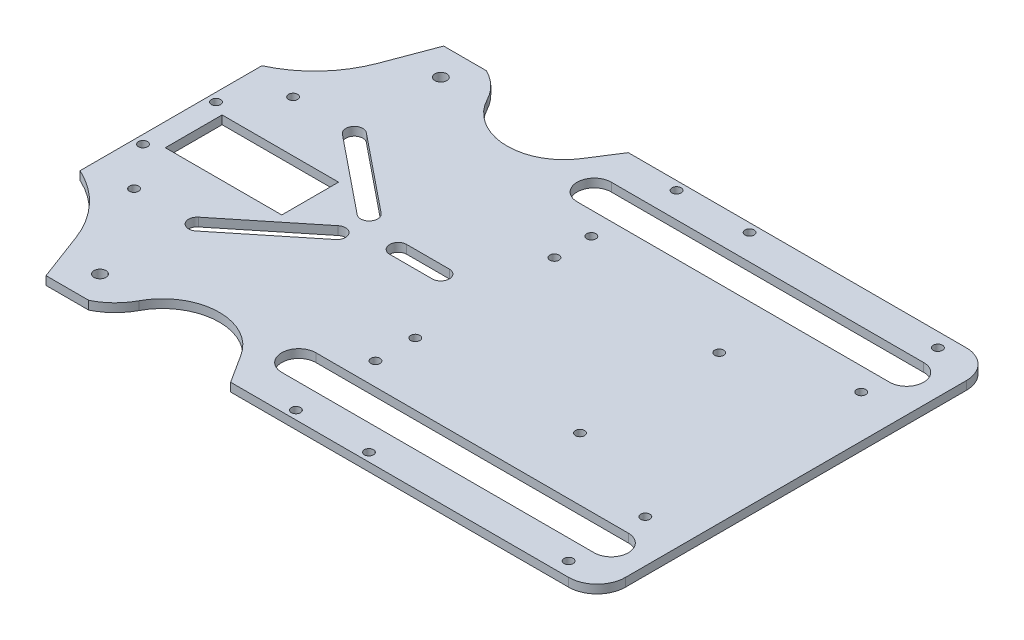
SolidWorks part; units mm, degrees
ref_plane "Front Plane" through (0, 0, 0) normal (0, 0, 1) x (1, 0, 0)
ref_plane "Top Plane" through (0, 0, 0) normal (0, 1, 0) x (1, 0, 0)
ref_plane "Right Plane" through (0, 0, 0) normal (1, 0, 0) x (0, 0, -1)
sketch "Çizim16" plane through (0, 0, 0) normal (0, 1, 0) x (1, 0, 0)
  line L1 (-110, -70) -> (100, -70)
  line L2 (-110, -70) -> (-110, 70)
  line L3 (-110, 70) -> (100, 70)
  line L4 (110, -60) -> (110, 60)
  line L5 (-110, -70) -> (110, 70) construction
  line L6 (-110, 70) -> (110, -70) construction
  arc A0 (100, -70) -> (110, -60) centre (100, -60) ccw
  arc A1 (100, 70) -> (110, 60) centre (100, 60) cw
  point P0 (0, 0)
  dimension "D3" = 10
  dimension "D1" = 220
  dimension "D2" = 140
extrude "Yükseklik-Ekstrüzyon3" add sketch "Çizim16" along normal blind 3
sketch "Çizim18" plane through (0, 3, 0) normal (0, 1, 0) x (1, 0, 0)
  line L0 (-19, 70) -> (-25.4638, 59.8897)
  line L1 (100, 70) -> (-110, 70) construction
  line L2 (-69, 70) -> (-19, 70)
  line L3 (-110, 70) -> (-110, -70) construction
  arc A0 (-25.4638, 59.8897) -> (-60, 61.3236) centre (-42.3144, 70.6627) cw
  arc A1 (-60, 61.3236) -> (-69, 70) centre (-77.6856, 51.9844) ccw
  dimension "D3" = 20
  dimension "D4" = 20
  dimension "D1" = 50
  dimension "D2" = 12
  dimension "D5" = 41
  dimension "D6" = 50
extrude "Kes-Ekstrüzyon10" cut sketch "Çizim18" against normal blind 3
sketch "Çizim19" plane through (0, 3, 0) normal (0, 1, 0) x (1, 0, 0)
  line L0 (-19, -70) -> (-25.4638, -59.8897)
  line L1 (-110, -70) -> (100, -70) construction
  line L2 (-69, -70) -> (-19, -70)
  line L3 (-110, 70) -> (-110, -70) construction
  arc A0 (-25.4638, -59.8897) -> (-60, -61.3236) centre (-42.3144, -70.6627) ccw
  arc A1 (-60, -61.3236) -> (-69, -70) centre (-77.6856, -51.9844) cw
  dimension "D1" = 20
  dimension "D3" = 20
  dimension "D2" = 12
  dimension "D4" = 50
  dimension "D5" = 41
  dimension "D6" = 50
extrude "Kes-Ekstrüzyon11" cut sketch "Çizim19" against normal blind 3
sketch "Çizim23" plane through (0, 3, 0) normal (0, 1, 0) x (1, 0, 0)
  line L0 (-84, -70) -> (-90.3297, -53.1496)
  line L1 (-110, -70) -> (-69, -70) construction
  line L2 (-110, 70) -> (-110, -70) construction
  line L3 (-110, -32) -> (-110, -70)
  line L4 (-110, -70) -> (-84, -70)
  arc A0 (-90.3297, -53.1496) -> (-110, -32) centre (-125.9027, -66.5124) ccw
  dimension "D2" = 38
  dimension "D1" = 18
  dimension "D3" = 38
  dimension "D4" = 26
extrude "Kes-Ekstrüzyon14" cut sketch "Çizim23" against normal blind 3
sketch "Çizim24" plane through (0, 3, 0) normal (0, 1, 0) x (1, 0, 0)
  line L0 (-84, 70) -> (-90.3297, 53.1496)
  line L1 (-69, 70) -> (-110, 70) construction
  line L2 (-110, 70) -> (-110, -32) construction
  line L3 (-110, 32) -> (-110, 70)
  line L4 (-110, 70) -> (-84, 70)
  arc A0 (-90.3297, 53.1496) -> (-110, 32) centre (-125.9027, 66.5124) cw
  dimension "D3" = 38
  dimension "D1" = 26
  dimension "D2" = 38
  dimension "D4" = 18
extrude "Kes-Ekstrüzyon15" cut sketch "Çizim24" against normal blind 3
sketch "Çizim25" plane through (0, 3, 0) normal (0, 1, 0) x (1, 0, 0)
  line L0 (-45.893, -5.6667) -> (-73.1143, -27.6667) construction
  line L1 (-44.0073, -8) -> (-71.2286, -30)
  line L2 (-47.7787, -3.3335) -> (-75, -25.3335)
  line L3 (-110, 32) -> (-110, -32) construction
  line L4 (-19, -70) -> (100, -70) construction
  line L5 (-84, -70) -> (-69, -70) construction
  arc A0 (-44.0073, -8) -> (-47.7787, -3.3335) centre (-45.893, -5.6667) ccw
  arc A1 (-75, -25.3335) -> (-71.2286, -30) centre (-73.1143, -27.6667) ccw
  point P2 (-59.5036, -16.6667)
  dimension "D2" = 3
  dimension "D4" = 62
  dimension "D1" = 35
  dimension "D3" = 35
  dimension "D5" = 40
extrude "Kes-Ekstrüzyon16" cut sketch "Çizim25" against normal blind 3
sketch "Çizim26" plane through (0, 3, 0) normal (0, 1, 0) x (1, 0, 0)
  line L0 (-73.1143, 27.6667) -> (-45.893, 5.6667) construction
  line L1 (-71.2286, 30) -> (-44.0073, 8)
  line L2 (-75, 25.3335) -> (-47.7787, 3.3335)
  line L6 (-69, 70) -> (-84, 70) construction
  line L7 (100, 70) -> (-19, 70) construction
  line L8 (-110, 32) -> (-110, -32) construction
  arc A0 (-71.2286, 30) -> (-75, 25.3335) centre (-73.1143, 27.6667) ccw
  arc A1 (-47.7787, 3.3335) -> (-44.0073, 8) centre (-45.893, 5.6667) ccw
  point P2 (-59.5036, 16.6667)
  dimension "D1" = 3
  dimension "D2" = 35
  dimension "D3" = 40
  dimension "D4" = 62
  dimension "D5" = 35
extrude "Kes-Ekstrüzyon17" cut sketch "Çizim26" against normal blind 3
sketch "Çizim27" plane through (0, 3, 0) normal (0, 1, 0) x (1, 0, 0)
  line L0 (-15, 0) -> (-30, 0) construction
  line L1 (-15, -3) -> (-30, -3)
  line L2 (-15, 3) -> (-30, 3)
  line L4 (-110, 32) -> (-110, -32) construction
  arc A0 (-15, -3) -> (-15, 3) centre (-15, 0) ccw
  arc A1 (-30, 3) -> (-30, -3) centre (-30, 0) ccw
  point P2 (-22.5, 0)
  dimension "D1" = 3
  dimension "D2" = 80
  dimension "D3" = 15
extrude "Kes-Ekstrüzyon18" cut sketch "Çizim27" against normal blind 3
sketch "Çizim28" plane through (0, 3, 0) normal (0, 1, 0) x (1, 0, 0)
  line L0 (-19, -70) -> (100, -70) construction
  circle A0 centre (1, -67) radius 1.6
  circle A1 centre (26.7, -67) radius 1.6
  dimension "D1" = 3.2
  dimension "D2" = 3.2
  dimension "D3" = 3
  dimension "D4" = 25.7
  dimension "D5" = 3
  dimension "D6" = 20
extrude "Kes-Ekstrüzyon19" cut sketch "Çizim28" against normal blind 3
sketch "Çizim29" plane through (0, 3, 0) normal (0, 1, 0) x (1, 0, 0)
  line L0 (-110, 32) -> (-110, -32) construction
  circle A0 centre (-107, 12.85) radius 1.6
  circle A1 centre (-107, -12.85) radius 1.6
  dimension "D1" = 3.2
  dimension "D2" = 3.2
  dimension "D3" = 25.7
  dimension "D4" = 3
  dimension "D5" = 3
  dimension "D6" = 19.15
extrude "Kes-Ekstrüzyon20" cut sketch "Çizim29" against normal blind 3
sketch "Çizim30" plane through (0, 3, 0) normal (0, 1, 0) x (1, 0, 0)
  line L0 (100, 70) -> (-19, 70) construction
  circle A0 centre (1, 67) radius 1.6
  circle A1 centre (26.7, 67) radius 1.6
  dimension "D1" = 3.2
  dimension "D2" = 3.2
  dimension "D3" = 3
  dimension "D4" = 3
  dimension "D5" = 25.7
  dimension "D6" = 20
extrude "Kes-Ekstrüzyon21" cut sketch "Çizim30" against normal blind 3
sketch "Çizim31" plane through (0, 3, 0) normal (0, 1, 0) x (1, 0, 0)
  line L0 (-69, 70) -> (-84, 70) construction
  line L1 (-102, -10) -> (-61, -10)
  line L2 (-102, -10) -> (-102, 10)
  line L3 (-102, 10) -> (-61, 10)
  line L4 (-61, -10) -> (-61, 10)
  line L5 (-102, -10) -> (-61, 10) construction
  line L6 (-102, 10) -> (-61, -10) construction
  line L7 (-110, 32) -> (-110, -32) construction
  point P0 (-81.5, 0)
  dimension "D1" = 41
  dimension "D2" = 20
  dimension "D3" = 60
  dimension "D4" = 8
extrude "Kes-Ekstrüzyon22" cut sketch "Çizim31" against normal blind 10
sketch "Çizim32" plane through (0, 3, 0) normal (0, 1, 0) x (1, 0, 0)
  line L0 (110, -60) -> (110, 60) construction
  line L1 (-19, -70) -> (100, -70) construction
  line L2 (100, 70) -> (-19, 70) construction
  line L3 (-84, -70) -> (-69, -70) construction
  line L4 (-110, 32) -> (-110, -32) construction
  line L5 (-69, 70) -> (-84, 70) construction
  circle A0 centre (95, -65) radius 1.6
  circle A1 centre (95, 65) radius 1.6
  circle A2 centre (-95, -28) radius 1.6
  circle A3 centre (-95, 28) radius 1.6
  dimension "D1" = 3.2
  dimension "D2" = 3.2
  dimension "D3" = 15
  dimension "D4" = 5
  dimension "D5" = 5
  dimension "D6" = 15
  dimension "D7" = 3.2
  dimension "D8" = 3.2
  dimension "D9" = 42
  dimension "D10" = 15
  dimension "D11" = 15
  dimension "D12" = 42
extrude "Kes-Ekstrüzyon23" cut sketch "Çizim32" against normal blind 10
sketch "Çizim33" plane through (0, 3, 0) normal (0, 1, 0) x (1, 0, 0)
  line L0 (97, 52) -> (-13, 52) construction
  line L1 (97, 46) -> (-13, 46)
  line L2 (97, 58) -> (-13, 58)
  line L3 (100, 70) -> (-19, 70) construction
  line L4 (110, -60) -> (110, 60) construction
  line L5 (-13, -52) -> (97, -52) construction
  line L6 (-13, -46) -> (97, -46)
  line L7 (-13, -58) -> (97, -58)
  line L8 (-19, -70) -> (100, -70) construction
  arc A0 (97, 46) -> (97, 58) centre (97, 52) ccw
  arc A1 (-13, 58) -> (-13, 46) centre (-13, 52) ccw
  arc A2 (-13, -46) -> (-13, -58) centre (-13, -52) ccw
  arc A3 (97, -58) -> (97, -46) centre (97, -52) ccw
  point P2 (42, 52)
  point P13 (42, -52)
  dimension "D2" = 6
  dimension "D4" = 13
  dimension "D5" = 6
  dimension "D8" = 13
  dimension "D1" = 110
  dimension "D3" = 12
  dimension "D6" = 110
  dimension "D7" = 12
extrude "Kes-Ekstrüzyon24" cut sketch "Çizim33" against normal blind 10
sketch "Çizim34" plane through (0, 3, 0) normal (0, 1, 0) x (1, 0, 0)
  line L0 (-84, -70) -> (-69, -70) construction
  line L1 (-110, 32) -> (-110, -32) construction
  line L2 (-69, 70) -> (-84, 70) construction
  circle A0 centre (-75, -60) radius 2.1
  circle A1 centre (-75, 60) radius 2.1
  dimension "D1" = 4.2
  dimension "D2" = 4.2
  dimension "D3" = 10
  dimension "D4" = 35
  dimension "D5" = 35
  dimension "D6" = 10
extrude "Kes-Ekstrüzyon25" cut sketch "Çizim34" against normal blind 3
sketch "Çizim35" plane through (0, 3, 0) normal (0, 1, 0) x (1, 0, 0)
  line L0 (97, -46) -> (-13, -46) construction
  line L1 (-13, 46) -> (97, 46) construction
  line L2 (110, -60) -> (110, 60) construction
  circle A0 centre (95, -38) radius 1.6
  circle A1 centre (95, 38) radius 1.6
  circle A2 centre (0, 38) radius 1.6
  circle A3 centre (0, -38) radius 1.6
  dimension "D1" = 3.2
  dimension "D2" = 3.2
  dimension "D3" = 3.2
  dimension "D4" = 3.2
  dimension "D5" = 8
  dimension "D6" = 8
  dimension "D7" = 8
  dimension "D9" = 15
  dimension "D11" = 15
  dimension "D12" = 110
  dimension "D8" = 8
  dimension "D10" = 110
extrude "Kes-Ekstrüzyon26" cut sketch "Çizim35" against normal blind 45
sketch "Çizim36" plane through (0, 3, 0) normal (0, 1, 0) x (1, 0, 0)
  line L0 (100, 70) -> (-19, 70) construction
  line L1 (110, -60) -> (110, 60) construction
  circle A0 centre (0, 25) radius 1.6
  circle A1 centre (58, 25) radius 1.6
  circle A2 centre (0, -24) radius 1.6
  circle A3 centre (58, -24) radius 1.6
  dimension "D1" = 3.2
  dimension "D2" = 3.2
  dimension "D3" = 3.2
  dimension "D4" = 3.2
  dimension "D5" = 58
  dimension "D6" = 58
  dimension "D7" = 45
  dimension "D8" = 52
  dimension "D9" = 52
  dimension "D10" = 49
  dimension "D11" = 49
  dimension "D12" = 45
extrude "Kes-Ekstrüzyon27" cut sketch "Çizim36" against normal blind 45
